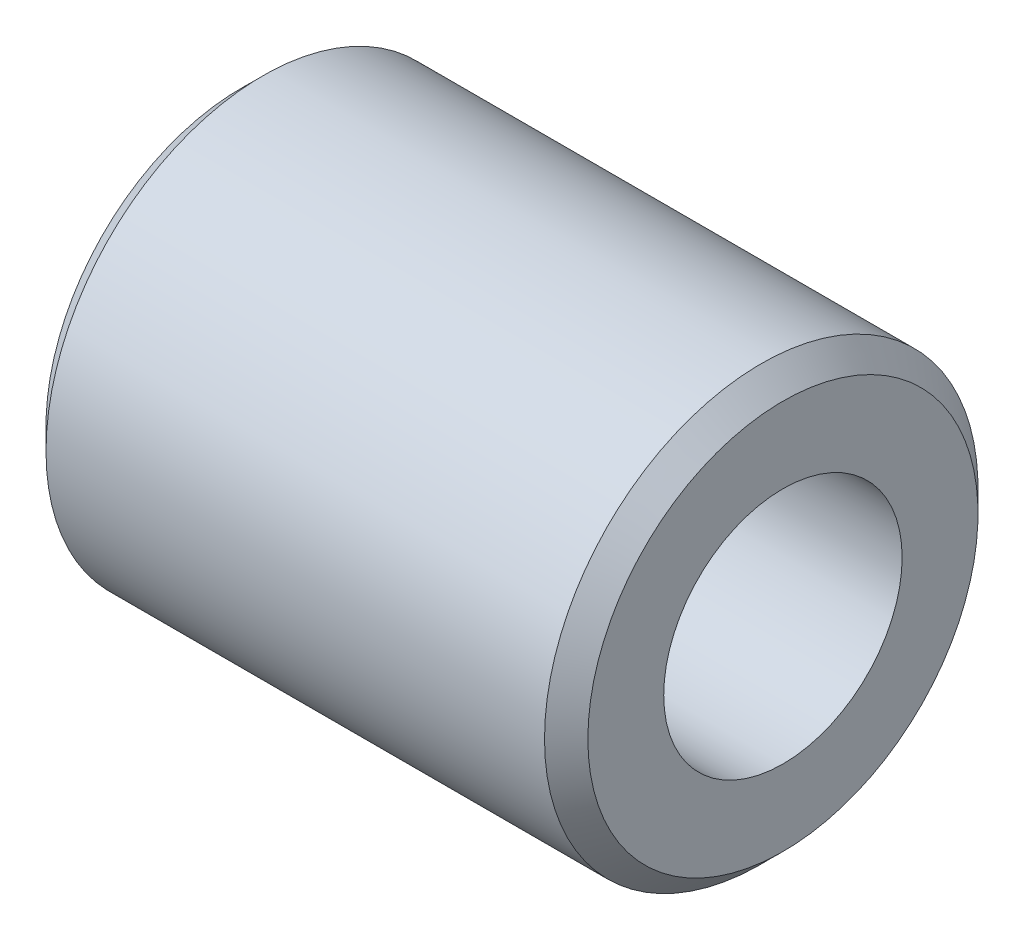
SolidWorks part; units mm, degrees
material "35"
ref_plane "前视基准面" through (0, 0, 0) normal (0, 0, 1) x (1, 0, 0)
ref_plane "上视基准面" through (0, 0, 0) normal (0, 1, 0) x (1, 0, 0)
ref_plane "右视基准面" through (0, 0, 0) normal (1, 0, 0) x (0, 0, -1)
sketch "草图1" plane through (0, 0, 0) normal (0, 0, 1) x (1, 0, 0)
  line L0 (0, 0) -> (201.9907, 0) construction
  line L1 (125, 27.5) -> (125, 50)
  line L2 (125, 50) -> (0, 50)
  line L3 (0, 50) -> (0, 27.5)
  line L4 (0, 27.5) -> (42, 27.5)
  line L5 (42, 27.5) -> (42, 30)
  line L6 (42, 30) -> (83, 30)
  line L7 (83, 30) -> (83, 27.5)
  line L8 (83, 27.5) -> (125, 27.5)
  line L9 (0, 27.5) -> (0, 0)
  dimension "D1" = 100
  dimension "D2" = 125
  dimension "D3" = 42
  dimension "D5" = 55
  dimension "D6" = 60
revolve "旋转1" add sketch "草图1" angle 360 about L0
chamfer "倒角1" distance 5 angle 45 2 edges at (125, 0, 50) (0, 0, 50)
